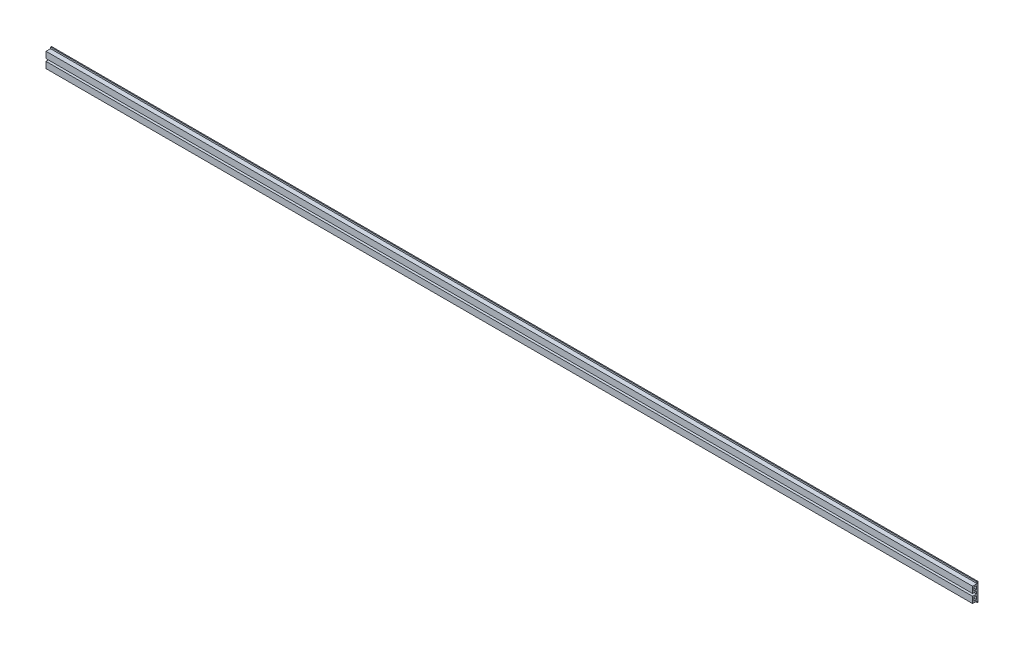
SolidWorks part; units mm, degrees
ref_plane "Спереди" through (0, 0, 0) normal (0, 0, 1) x (1, 0, 0)
ref_plane "Сверху" through (0, 0, 0) normal (0, 1, 0) x (1, 0, 0)
ref_plane "Справа" through (0, 0, 0) normal (1, 0, 0) x (0, 0, -1)
sketch "Эскиз1" plane through (0, 0, 0) normal (1, 0, 0) x (0, 0, -1)
  line L0 (0, -30) -> (0, 30)
  line L1 (0, 30) -> (-3, 30)
  line L2 (-3, 30) -> (-3, 25)
  line L3 (-3, 25) -> (-18, 25)
  line L4 (-18, 25) -> (-18, 4)
  line L5 (-18, 4) -> (-5, 4)
  line L6 (-5, 4) -> (-5, -4)
  line L7 (-5, -4) -> (-18, -4)
  line L8 (-18, -4) -> (-18, -25)
  line L9 (-18, -25) -> (-3, -25)
  line L10 (-3, -25) -> (-3, -30)
  line L11 (-3, -30) -> (0, -30)
  line L12 (0, 0) -> (-42.5697, 0) construction
  line L13 (-5, 20) -> (-13, 20)
  line L14 (-13, 20) -> (-13, 9)
  line L15 (-13, 9) -> (-5, 9)
  line L16 (-5, -9) -> (-13, -9)
  line L17 (-13, -9) -> (-13, -20)
  line L18 (-13, -20) -> (-5, -20)
  line L19 (-5, 9) -> (-5, 20)
  line L20 (-5, -9) -> (-5, -20)
  line L22 (-13, -20) -> (-3, -20) construction
  line L23 (-3, 20) -> (-13, 20) construction
  point P16 (0, 0)
  dimension "D1" = 60
  dimension "D2" = 5
  dimension "D3" = 8
  dimension "D4" = 3
  dimension "D5" = 5
  dimension "D6" = 18
  dimension "D7" = 5
extrude "Бобышка-Вытянуть1" add sketch "Эскиз1" against normal up to surface (3080 mm away)
